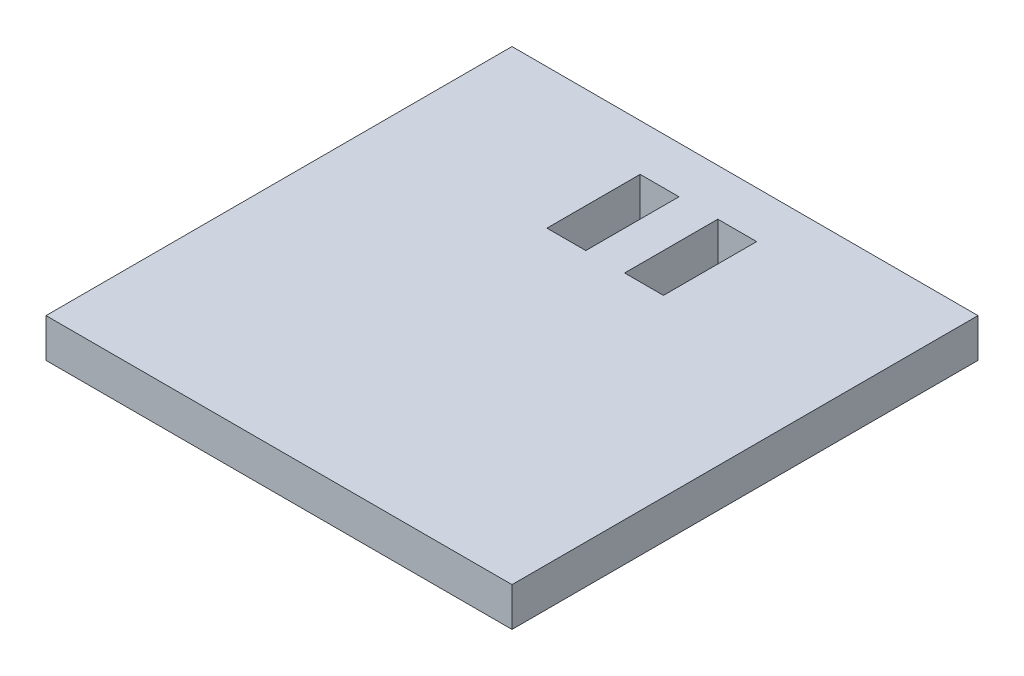
SolidWorks part; units mm, degrees
ref_plane "Front Plane" through (0, 0, 0) normal (0, 0, 1) x (1, 0, 0)
ref_plane "Top Plane" through (0, 0, 0) normal (0, 1, 0) x (1, 0, 0)
ref_plane "Right Plane" through (0, 0, 0) normal (1, 0, 0) x (0, 0, -1)
sketch "Sketch1" plane through (0, 0, 0) normal (0, 1, 0) x (1, 0, 0)
  line L1 (0, 0) -> (38.1, 0)
  line L2 (0, 0) -> (0, 38.1)
  line L3 (0, 38.1) -> (38.1, 38.1)
  line L4 (38.1, 0) -> (38.1, 38.1)
  line L5 (14.2875, 34.29) -> (17.4625, 34.29)
  line L6 (14.2875, 34.29) -> (14.2875, 26.67)
  line L7 (14.2875, 26.67) -> (17.4625, 26.67)
  line L8 (17.4625, 34.29) -> (17.4625, 26.67)
  line L9 (20.6375, 34.29) -> (23.8125, 34.29)
  line L10 (20.6375, 34.29) -> (20.6375, 26.67)
  line L11 (20.6375, 26.67) -> (23.8125, 26.67)
  line L12 (23.8125, 34.29) -> (23.8125, 26.67)
  point P9 (14.2875, 30.48)
  dimension "D1" = 38.1
  dimension "D2" = 38.1
  dimension "D3" = 7.62
  dimension "D4" = 3.175
  dimension "D5" = 14.2875
  dimension "D6" = 3.81
  dimension "D7" = 7.62
  dimension "D8" = 3.175
  dimension "D9" = 3.81
  dimension "D10" = 14.2875
extrude "Boss-Extrude1" add sketch "Sketch1" along normal blind 3.175
